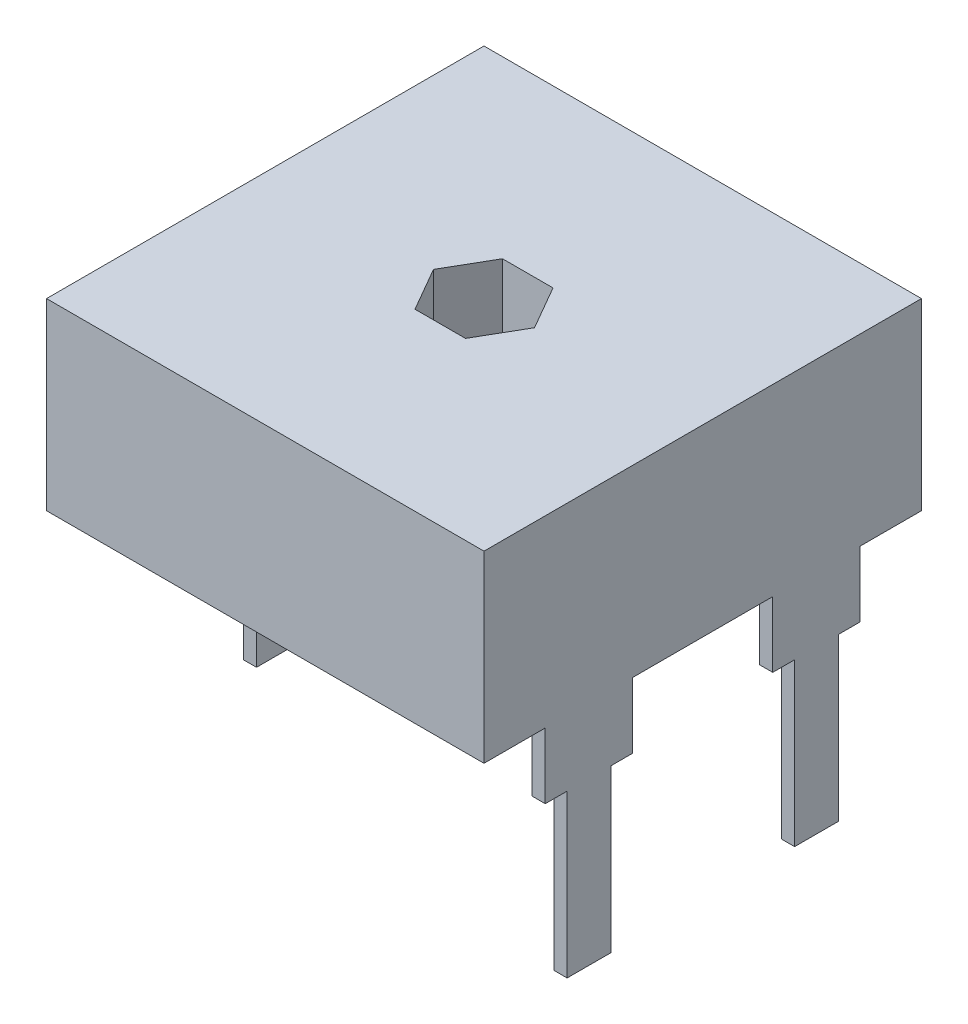
SolidWorks part; units mm, degrees
ref_plane "Front Plane" through (0, 0, 0) normal (0, 0, 1) x (1, 0, 0)
ref_plane "Top Plane" through (0, 0, 0) normal (0, 1, 0) x (1, 0, 0)
ref_plane "Right Plane" through (0, 0, 0) normal (1, 0, 0) x (0, 0, -1)
sketch "Sketch1" plane through (0, 0, 0) normal (0, 1, 0) x (1, 0, 0)
  line L1 (-5, -5) -> (5, -5)
  line L2 (-5, -5) -> (-5, 5)
  line L3 (-5, 5) -> (5, 5)
  line L4 (5, -5) -> (5, 5)
  line L5 (-5, -5) -> (5, 5) construction
  line L6 (-5, 5) -> (5, -5) construction
  point P0 (0, 0)
  dimension "D1" = 10
  dimension "D2" = 10
extrude "Boss-Extrude1" add sketch "Sketch1" against normal blind 4.2
sketch "Sketch2" plane through (0, 0, 0) normal (0, 1, 0) x (1, 0, 0)
  line L1 (1.1547, 0) -> (0.5774, 1)
  line L2 (0.5774, 1) -> (-0.5774, 1)
  line L3 (-0.5774, 1) -> (-1.1547, 0)
  line L4 (-1.1547, 0) -> (-0.5774, -1)
  line L5 (-0.5774, -1) -> (0.5774, -1)
  line L6 (0.5774, -1) -> (1.1547, 0)
  circle A0 centre (0, 0) radius 1 construction
  point P1 (0.6996, -0.9187)
  point P10 (0, 0)
  dimension "D1" = 2
extrude "Cut-Extrude1" cut sketch "Sketch2" against normal up to next
sketch "Sketch3" plane through (0, -4.2, 0) normal (0, -1, 0) x (1, 0, 0)
  line L0 (5, 5) -> (5, -5) construction
  line L1 (5, 3.6) -> (4.7, 3.6)
  line L2 (5, 3.6) -> (5, 1.6)
  line L3 (5, 1.6) -> (4.7, 1.6)
  line L4 (4.7, 3.6) -> (4.7, 1.6)
  line L5 (-5, -5) -> (-5, 5) construction
  line L6 (5, -3.6) -> (4.7, -3.6)
  line L7 (5, -3.6) -> (5, -1.6)
  line L8 (5, -1.6) -> (4.7, -1.6)
  line L9 (4.7, -3.6) -> (4.7, -1.6)
  line L10 (-5, 1) -> (-4.7, 1)
  line L11 (-5, 1) -> (-5, -1)
  line L12 (-5, -1) -> (-4.7, -1)
  line L13 (-4.7, 1) -> (-4.7, -1)
  point P16 (-4.7, 0)
  dimension "D2" = 2
  dimension "D3" = 2
  dimension "D4" = 0.3
  dimension "D5" = 0.3
  dimension "D6" = 0.3
  dimension "D7" = 2
  dimension "D1" = 3.6
  dimension "D8" = 3.6
extrude "Boss-Extrude2" add sketch "Sketch3" along normal blind 1.5
sketch "Sketch4" plane through (0, -5.7, 0) normal (0, -1, 0) x (1, 0, 0)
  line L5 (4.7, -1.6) -> (4.7, -3.6) construction
  line L6 (4.7, -3.1) -> (5, -3.1)
  line L7 (4.7, -3.1) -> (4.7, -2.1)
  line L8 (4.7, -2.1) -> (5, -2.1)
  line L9 (5, -3.1) -> (5, -2.1)
  line L10 (5, -3.6) -> (5, -1.6) construction
  line L11 (-5, 1) -> (-5, -1) construction
  line L12 (-5, -0.5) -> (-4.7, -0.5)
  line L13 (-5, -0.5) -> (-5, 0.5)
  line L14 (-5, 0.5) -> (-4.7, 0.5)
  line L15 (-4.7, -0.5) -> (-4.7, 0.5)
  line L16 (-4.7, -1) -> (-4.7, 1) construction
  line L17 (4.7, 3.6) -> (4.7, 1.6) construction
  line L18 (4.7, 2.1) -> (5, 2.1)
  line L19 (4.7, 2.1) -> (4.7, 3.1)
  line L20 (4.7, 3.1) -> (5, 3.1)
  line L21 (5, 2.1) -> (5, 3.1)
  line L22 (5, 1.6) -> (5, 3.6) construction
  point P22 (-4.7, 0)
  point P23 (-4.7, 0)
  point P26 (5, 2.6)
  point P27 (5, 2.6)
  point P28 (5, -2.6)
  point P29 (5, -2.6)
  dimension "D1" = 1
  dimension "D2" = 1
  dimension "D3" = 1
extrude "Boss-Extrude3" add sketch "Sketch4" along normal blind 3.7
equation "\"D2@Sketch1\"=\"D1@Sketch1\""
equation "\"D3@Sketch3\"=\"D2@Sketch3\""
equation "\"D5@Sketch3\"=\"D4@Sketch3\""
equation "\"D6@Sketch3\"=\"D4@Sketch3\""
equation "\"D7@Sketch3\"=\"D2@Sketch3\""
equation "\"D8@Sketch3\"=\"D1@Sketch3\""
